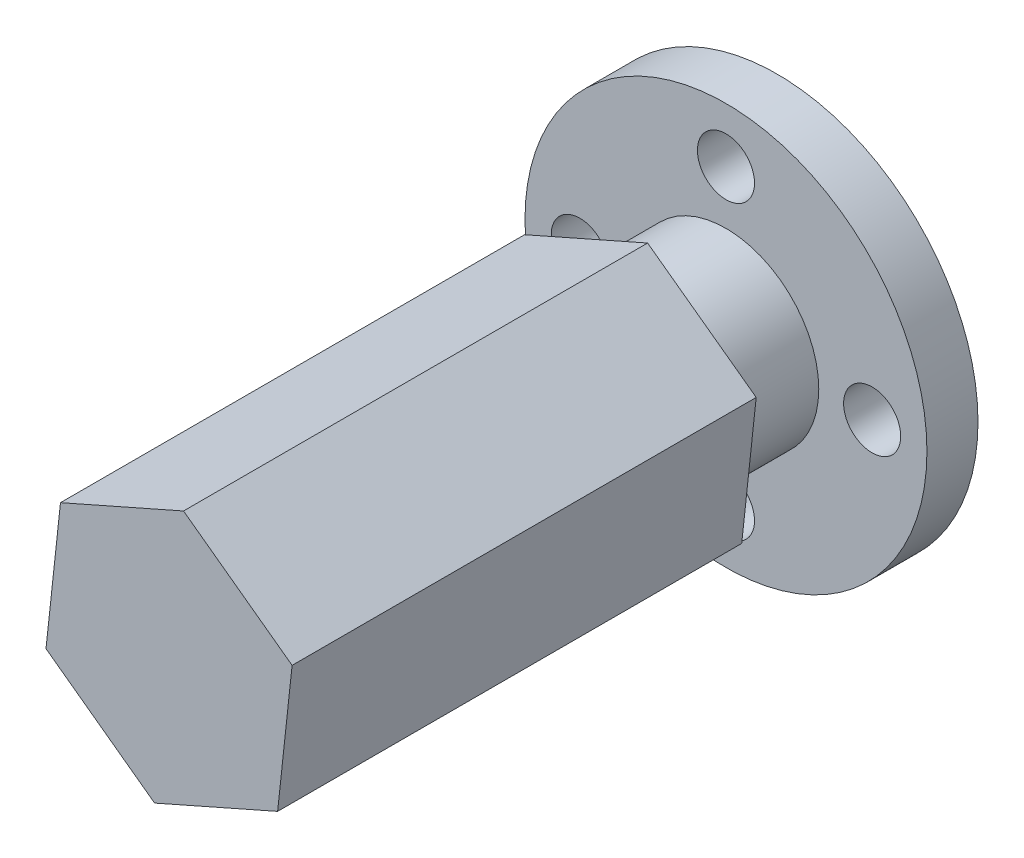
SolidWorks part; units mm, degrees
ref_plane "Front Plane" through (0, 0, 0) normal (0, 0, 1) x (1, 0, 0)
ref_plane "Top Plane" through (0, 0, 0) normal (0, 1, 0) x (1, 0, 0)
ref_plane "Right Plane" through (0, 0, 0) normal (1, 0, 0) x (0, 0, -1)
sketch "Sketch1" plane through (0, 0, 0) normal (0, 0, 1) x (1, 0, 0)
  circle A9 centre (-211.6729, 6.3572) radius 11
  circle A10 centre (-211.6729, 6.3572) radius 4.1984
  circle A11 centre (-211.6729, 14.3582) radius 1.5624
  circle A12 centre (-219.6739, 6.3572) radius 1.5624
  circle A13 centre (-211.6729, -1.6438) radius 1.5624
  circle A14 centre (-203.6719, 6.3572) radius 1.5624
  dimension "D1" = 8.001
  dimension "D2" = 3.1247
  dimension "D3" = 22
  dimension "D4" = 8.3969
  dimension "D5" = 3.1247
  dimension "D6" = 3.1247
  dimension "D7" = 3.1247
  dimension "D8" = 8.001
  dimension "D9" = 8.001
  dimension "D10" = 8.001
extrude "Boss-Extrude1" add sketch "Sketch1" along normal blind 2.794
sketch "Sketch4" plane through (0, 0, 2.794) normal (0, 0, 1) x (1, 0, 0)
  circle A0 centre (-211.6729, 6.3572) radius 5.08
extrude "Boss-Extrude2" add sketch "Sketch4" along normal blind 5.08
sketch "Sketch6" plane through (0, 0, 7.874) normal (0, 0, 1) x (1, 0, 0)
  line L0 (-217.6149, 10.7031) -> (-210.8802, 13.6761)
  line L1 (-210.8802, 13.6761) -> (-204.9382, 9.3302)
  line L2 (-204.9382, 9.3302) -> (-205.7309, 2.0113)
  line L3 (-205.7309, 2.0113) -> (-212.4656, -0.9617)
  line L4 (-212.4656, -0.9617) -> (-218.4076, 3.3842)
  line L5 (-218.4076, 3.3842) -> (-217.6149, 10.7031)
extrude "Boss-Extrude4" add sketch "Sketch6" along normal blind 25.4
